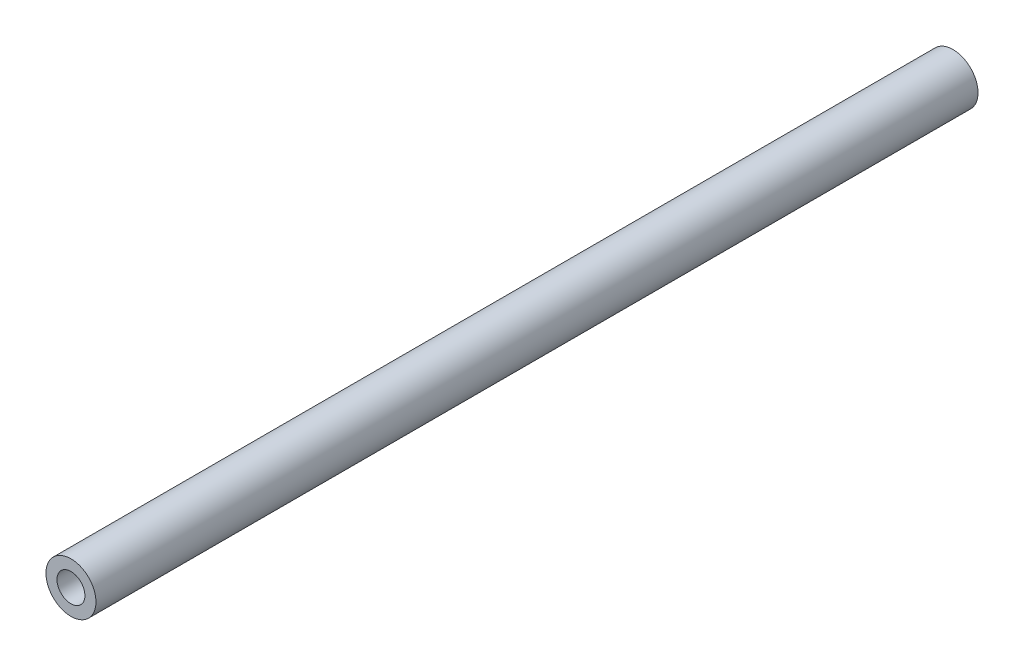
SolidWorks part; units mm, degrees
material "Polieter Polyol"
ref_plane "Ön Düzlem" through (0, 0, 0) normal (0, 0, 1) x (1, 0, 0)
ref_plane "Üst Düzlem" through (0, 0, 0) normal (0, 1, 0) x (1, 0, 0)
ref_plane "Sağ Düzlem" through (0, 0, 0) normal (1, 0, 0) x (0, 0, -1)
sketch "Çizim1" plane through (0, 0, 0) normal (0, 0, 1) x (1, 0, 0)
  circle A0 centre (0, 0) radius 4.75
  circle A1 centre (0, 0) radius 8.5
  dimension "D1" = 17
  dimension "D2" = 9.5
extrude "Yükseklik-Ekstrüzyon1" add sketch "Çizim1" along normal blind 300
